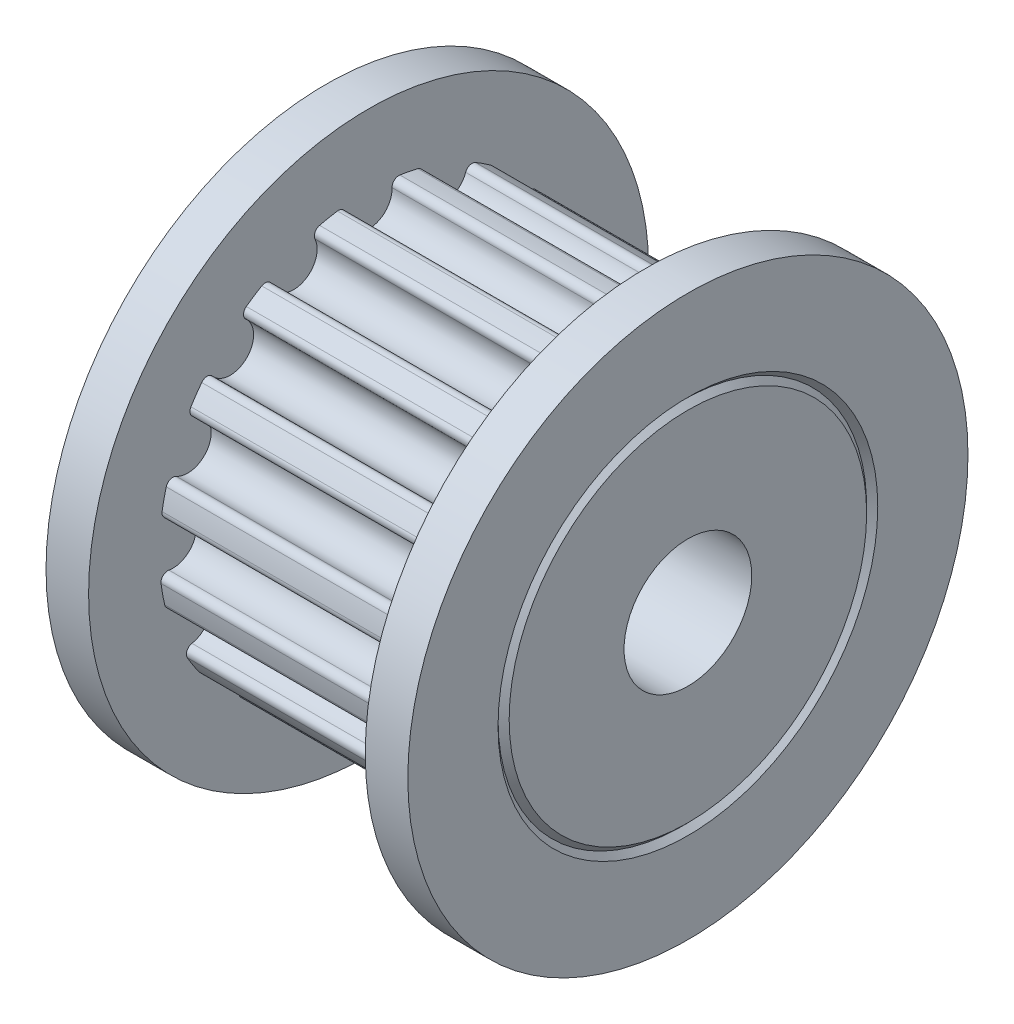
SolidWorks part; units mm, degrees
other "Pulley" parameters "D16"=0.5
material "6061-O (SS)"
ref_plane "Сверху" through (0, 0, 0) normal (0, 0, 1) x (1, 0, 0)
ref_plane "Справа" through (0, 0, 0) normal (0, 1, 0) x (1, 0, 0)
ref_plane "Спереди" through (0, 0, 0) normal (1, 0, 0) x (0, 0, -1)
sketch "Эскиз1" plane through (0, 0, 0) normal (0, 0, 1) x (1, 0, 0)
  line L1 (5.6, 4.1193) -> (5.7307, 4.25)
  line L2 (5.7307, 4.25) -> (5.6, 4.3807)
  line L3 (5.6, 6.5) -> (6.6, 6.5)
  line L4 (6.6, 4.84) -> (13.1, 4.84)
  line L5 (13.1, 4.84) -> (13.1, 6.5)
  line L6 (13.1, 6.5) -> (14.1, 6.5)
  line L7 (14.1, -0.08) -> (14.1, 4.1193)
  line L8 (14.1, 4.1193) -> (13.9693, 4.25)
  line L9 (13.9693, 4.25) -> (14.1, 4.3807)
  line L10 (14.1, 4.3807) -> (14.1, 6.5)
  line L11 (5.6, -0.08) -> (14.1, -0.08)
  line L12 (6.6, 6.5) -> (6.6, 4.84)
  line L13 (5.6, 6.5) -> (5.6, 4.3807)
  line L14 (5.6, 4.1193) -> (5.6, -0.08)
  dimension "D1" = 1
  dimension "D2" = 4.92
  dimension "D5" = 1
  dimension "D8" = 6.5
revolve "Body" add sketch "Эскиз1" angle 360 about L11
sketch "Эскиз2" plane through (14.1, 0, 0) normal (1, 0, 0) x (0, 0, -1)
  circle A0 centre (0, 0) radius 1.5
  dimension "D1" = 3
extrude "Bore" cut sketch "Эскиз2" against normal through all
sketch "Эскиз3" plane through (6.6, 0, 0) normal (1, 0, 0) x (0, 0, -1)
  line L0 (0, 0) -> (9.7637, 0) construction
  circle A0 centre (4.2498, -1.7603) radius 0.55
  circle A1 centre (0, 0) radius 5.15 construction
  circle A2 centre (3.2527, -3.2527) radius 0.55
  circle A3 centre (1.7603, -4.2498) radius 0.55
  circle A4 centre (0, -4.6) radius 0.55
  circle A5 centre (-1.7603, -4.2498) radius 0.55
  circle A6 centre (4.6, 0) radius 0.55
  circle A7 centre (-3.2527, -3.2527) radius 0.55
  circle A8 centre (-4.2498, -1.7603) radius 0.55
  circle A9 centre (-4.6, 0) radius 0.55
  circle A10 centre (-4.2498, 1.7603) radius 0.55
  circle A11 centre (-3.2527, 3.2527) radius 0.55
  circle A12 centre (-1.7603, 4.2498) radius 0.55
  circle A13 centre (0, 4.6) radius 0.55
  circle A14 centre (1.7603, 4.2498) radius 0.55
  circle A17 centre (3.2527, 3.2527) radius 0.55
  circle A18 centre (4.2498, 1.7603) radius 0.55
  point P45 (0, 0)
  dimension "D1" = 10.3
  dimension "D2" = 16
  dimension "D3" = 1.1
extrude "16t" cut sketch "Эскиз3" along normal up to surface (6.5 mm away) up to face at (13.1, -0.08, 6.58)
fillet "Fillet" radius 0.16 32 edges at (9.85, 0.4677, -4.8894) (9.85, -0.4573, -4.9055) (9.85, -1.4729, -4.7187) (9.85, -2.2908, -4.3953) (9.85, -3.2044, -3.8006) (9.85, -3.8016, -3.2181) (9.85, -4.4421, -2.2757) (9.85, -4.7532, -1.5387) (9.85, -4.9842, -0.3935) (9.85, -4.9842, 0.3935) (9.85, -4.7532, 1.5387) (9.85, -4.4421, 2.2757) (9.85, -3.8016, 3.2181) (9.85, -3.2044, 3.8006) (9.85, -2.2908, 4.3953) (9.85, -1.4729, 4.7187) (9.85, -0.4573, 4.9055) (9.85, 0.4677, 4.8894) (9.85, 1.4235, 4.6846) (9.85, 2.3079, 4.3017) (9.85, 3.0767, 3.7738) (9.85, 3.7694, 3.0641) (9.85, 4.2639, 2.3102) (9.85, 4.6436, 1.3763) (9.85, 4.8138, 0.5067) (9.85, 4.8138, -0.5067) (9.85, 4.6436, -1.3763) (9.85, 4.2639, -2.3102) (9.85, 3.7694, -3.0641) (9.85, 3.0767, -3.7738) (9.85, 2.3079, -4.3017) (9.85, 1.4235, -4.6846)
